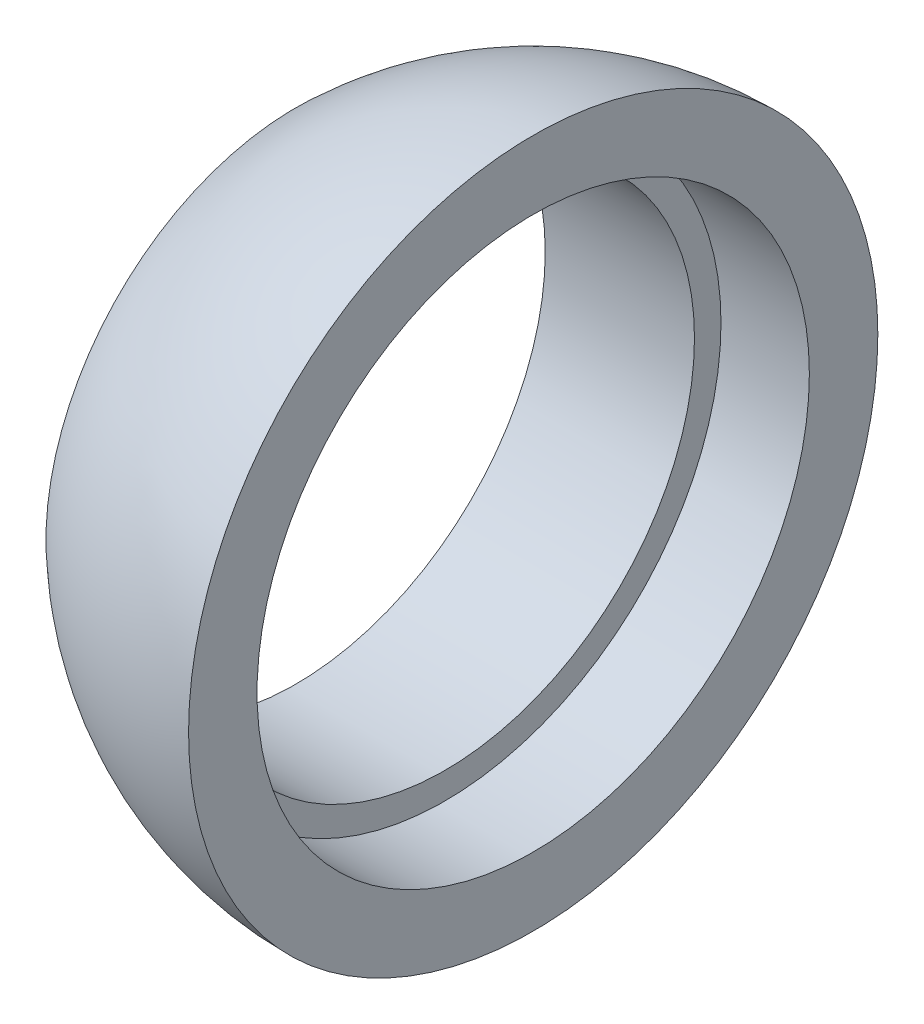
SolidWorks part; units mm, degrees
ref_plane "前视基准面" through (0, 0, 0) normal (0, 0, 1) x (1, 0, 0)
ref_plane "上视基准面" through (0, 0, 0) normal (0, 1, 0) x (1, 0, 0)
ref_plane "右视基准面" through (0, 0, 0) normal (1, 0, 0) x (0, 0, -1)
other "Configuration Table"
sketch "草图1" plane through (0, 0, 0) normal (1, 0, 0) x (0, 0, -1)
  line L0 (0, 7.8) -> (0, -7.8)
  arc A0 (0, 7.8) -> (0, -7.8) centre (0, 0) ccw
  dimension "D1" = 7.8
revolve "旋转1" add sketch "草图1" angle 180 about L0
sketch "草图5" plane through (0, 0, 0) normal (0, 0, 1) x (1, 0, 0)
  line L0 (0, -7.8) -> (0, 7.8) construction
  line L1 (-11.5, 10.097) -> (-5.5, 10.097)
  line L2 (-11.5, 10.097) -> (-11.5, -9.903)
  line L3 (-11.5, -9.903) -> (-5.5, -9.903)
  line L4 (-5.5, 10.097) -> (-5.5, -9.903)
  dimension "D1" = 20
  dimension "D2" = 5.5
  dimension "D3" = 6
extrude "切除-拉伸3" cut sketch "草图5" against normal through all and the other way through all
sketch "草图11" plane through (0, 0, 0) normal (1, 0, 0) x (0, 0, -1)
  circle A0 centre (0, 0) radius 5.65
  dimension "D1" = 11.3
extrude "切除-拉伸7" cut sketch "草图11" against normal through all
sketch "草图12" plane through (0, 0, 0) normal (1, 0, 0) x (0, 0, -1)
  circle A0 centre (0, 0) radius 6.25
  dimension "D1" = 12.5
extrude "切除-拉伸8" cut sketch "草图12" against normal blind 2
